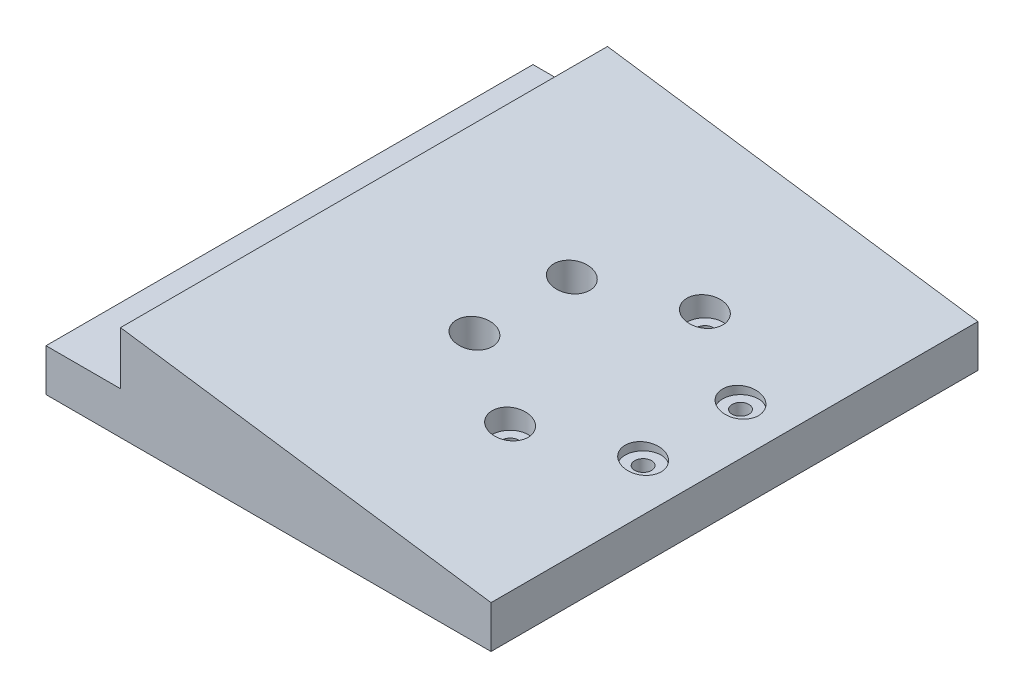
SolidWorks part; units mm, degrees
ref_plane "Front Plane" through (0, 0, 0) normal (0, 0, 1) x (1, 0, 0)
ref_plane "Top Plane" through (0, 0, 0) normal (0, 1, 0) x (1, 0, 0)
ref_plane "Right Plane" through (0, 0, 0) normal (1, 0, 0) x (0, 0, -1)
sketch "Sketch1" plane through (0, 0, 0) normal (0, 1, 0) x (1, 0, 0)
  line L1 (-52.55, 57.5) -> (52.55, 57.5)
  line L2 (-52.55, 57.5) -> (-52.55, -57.5)
  line L3 (-52.55, -57.5) -> (52.55, -57.5)
  line L4 (52.55, 57.5) -> (52.55, -57.5)
  line L5 (-52.55, 57.5) -> (52.55, -57.5) construction
  line L6 (-52.55, -57.5) -> (52.55, 57.5) construction
  point P0 (0, 0)
  dimension "D1" = 115
  dimension "D2" = 105.1
extrude "Boss-Extrude1" add sketch "Sketch1" along normal blind 10
sketch "Sketch3" plane through (0, 0, 57.5) normal (0, 0, 1) x (1, 0, 0)
  line L0 (-34.95, 10) -> (52.55, 10)
  line L1 (-52.55, 10) -> (52.55, 10) construction
  line L2 (52.55, 10) -> (-34.95, 22.5)
  line L3 (-34.95, 22.5) -> (-34.95, 10)
  point P5 (0, 0)
extrude "Boss-Extrude2" add sketch "Sketch3" against normal blind 115
sketch "Sketch2" plane through (0, 0, 0) normal (0, -1, 0) x (1, 0, 0)
  line L0 (52.55, 57.5) -> (52.55, -57.5) construction
  circle A0 centre (22.55, 0) radius 30 construction
  circle A1 centre (22.55, 0) radius 23 construction
  circle A2 centre (22.55, 23) radius 2
  circle A3 centre (2.6314, 11.5) radius 2
  circle A4 centre (2.6314, -11.5) radius 2
  circle A5 centre (22.55, -23) radius 2
  circle A6 centre (42.4686, -11.5) radius 2
  circle A7 centre (42.4686, 11.5) radius 2
  point P19 (22.55, 0)
  dimension "D1" = 60
  dimension "D2" = 46
  dimension "D3" = 4
  dimension "D4" = 6
extrude "Cut-Extrude1" cut sketch "Sketch2" against normal blind 20
ref_plane "Plane1" through (0, 50, 0) normal (0, -1, 0) x (-1, 0, 0)
sketch "Sketch4" plane through (0, 50, 0) normal (0, -1, 0) x (-1, 0, 0)
  line L0 (-52.55, -57.5) -> (-52.55, 57.5) construction
  circle A0 centre (-22.55, 0) radius 30 construction
  circle A1 centre (-22.55, 0) radius 23 construction
  circle A2 centre (-22.55, 23) radius 4.25
  circle A3 centre (-2.6314, 11.5) radius 4.25
  circle A4 centre (-2.6314, -11.5) radius 4.25
  circle A5 centre (-22.55, -23) radius 4.25
  circle A6 centre (-42.4686, -11.5) radius 4.25
  circle A7 centre (-42.4686, 11.5) radius 4.25
  point P19 (-22.55, 0)
  dimension "D1" = 60
  dimension "D2" = 46
  dimension "D3" = 8.5
  dimension "D4" = 6
extrude "Cut-Extrude2" cut sketch "Sketch4" along normal blind 40
